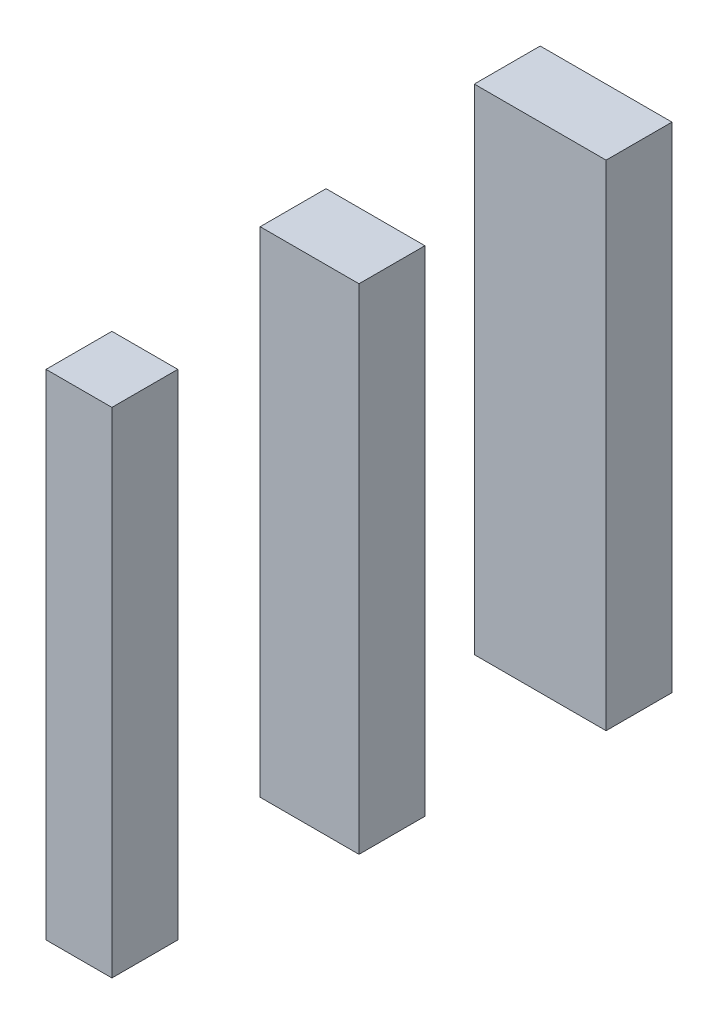
SolidWorks part; units mm, degrees
ref_plane "Front Plane" through (0, 0, 0) normal (0, 0, 1) x (1, 0, 0)
ref_plane "Top Plane" through (0, 0, 0) normal (0, 1, 0) x (1, 0, 0)
ref_plane "Right Plane" through (0, 0, 0) normal (1, 0, 0) x (0, 0, -1)
sketch "Sketch1" plane through (0, 0, 0) normal (0, 1, 0) x (1, 0, 0)
  line L1 (25, -25) -> (-25, -25)
  line L2 (25, -25) -> (25, 25)
  line L3 (25, 25) -> (-25, 25)
  line L4 (-25, -25) -> (-25, 25)
  line L5 (25, -25) -> (-25, 25) construction
  line L6 (25, 25) -> (-25, -25) construction
  point P0 (0, 0)
  dimension "D1" = 50
  dimension "D2" = 50
ref_plane "Plane2" through (0, 1, 0) normal (0, 1, 0) x (1, 0, 0)
sketch "Sketch2" plane through (0, 1, 0) normal (0, 1, 0) x (1, 0, 0)
  line L0 (0, 12) -> (0, -20.9373) construction
  line L1 (-2, -12) -> (2, -12)
  line L2 (-2, -12) -> (-2, -16)
  line L3 (-2, -16) -> (2, -16)
  line L4 (2, -12) -> (2, -16)
  line L5 (-2, -14) -> (2, -14) construction
  line L7 (-3, 2) -> (3, 2)
  line L8 (-3, 2) -> (-3, -2)
  line L9 (-3, -2) -> (3, -2)
  line L10 (3, 2) -> (3, -2)
  line L11 (-3, 0) -> (3, 0) construction
  line L12 (-4, 16) -> (4, 16)
  line L13 (-4, 16) -> (-4, 12)
  line L14 (-4, 12) -> (4, 12)
  line L15 (4, 16) -> (4, 12)
  line L16 (0, 16) -> (0, 12) construction
  point P8 (0, 0)
  point P21 (0, -14)
  point P22 (0, 0)
  point P23 (0, 0)
  point P24 (0, 0)
  dimension "D1" = 4
  dimension "D2" = 4
  dimension "D5" = 6
  dimension "D6" = 4
  dimension "D7" = 10
  dimension "D9" = 4
  dimension "D10" = 8
  dimension "D12" = 10
extrude "Boss-Extrude1" add sketch "Sketch2" along normal blind 30
